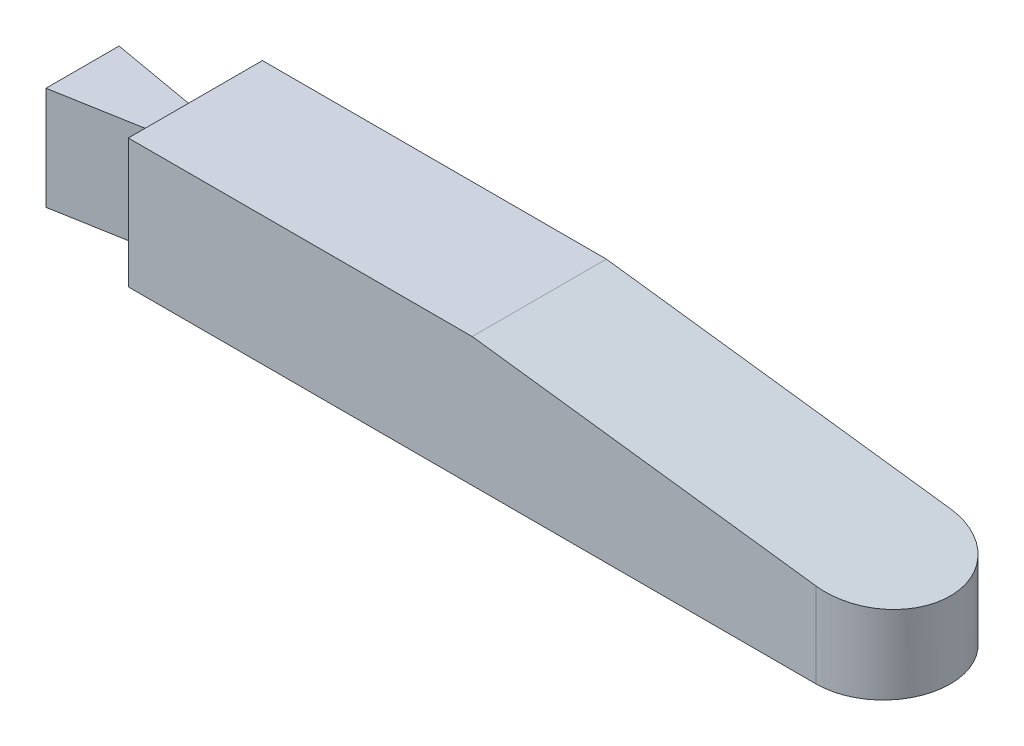
SolidWorks part; units mm, degrees
ref_plane "Front Plane" through (0, 0, 0) normal (0, 0, 1) x (1, 0, 0)
ref_plane "Top Plane" through (0, 0, 0) normal (0, 1, 0) x (1, 0, 0)
ref_plane "Right Plane" through (0, 0, 0) normal (1, 0, 0) x (0, 0, -1)
sketch "Sketch2" plane through (0, 0, 0) normal (0, 1, 0) x (1, 0, 0)
  line L10 (18.9628, -17.9605) -> (18.9628, -28.085) construction
  line L29 (-13.5492, -12.2277) -> (-13.5492, -33.8177)
  line L30 (-13.5492, -12.2277) -> (18.9628, -17.9605)
  line L31 (-13.5492, -33.8177) -> (18.9628, -28.085)
  line L32 (18.9628, -2.3886) -> (222.1628, -2.3886)
  line L33 (18.9628, -42.0126) -> (222.1628, -42.0126)
  line L35 (18.9628, -2.3886) -> (18.9628, -17.9605)
  line L36 (18.9628, -42.0126) -> (18.9628, -28.085)
  line L37 (-13.5492, -23.0227) -> (18.9628, -23.0227) construction
  arc A5 (222.1628, -2.3886) -> (222.1628, -42.0126) centre (222.1628, -22.2006) cw
  dimension "D4" = 80
  dimension "D5" = 39.624
  dimension "D3" = 80
  dimension "D2" = 21.59
  dimension "D6" = 203.2
  dimension "D9" = 13.5492
  dimension "D10" = 26.1183
  dimension "D11" = 13.9276
  dimension "D14" = 32.512
extrude "Boss-Extrude1" add sketch "Sketch2" along normal blind 38.1
sketch "Sketch3" plane through (0, 38.1, 0) normal (0, 1, 0) x (1, 0, 0)
  line L0 (-13.5492, -12.2277) -> (-13.5492, -33.8177)
  line L1 (-13.5492, -33.8177) -> (18.9628, -28.085)
  line L2 (18.9628, -28.085) -> (18.9628, -17.9605)
  line L3 (18.9628, -17.9605) -> (-13.5492, -12.2277)
extrude "Cut-Extrude1" cut sketch "Sketch3" against normal blind 7.62
sketch "Sketch5" plane through (0, 0, 42.0126) normal (0, 0, 1) x (1, 0, 0)
  line L5 (120.5628, 38.1) -> (241.9748, 22.5197)
  line L6 (18.9628, 38.1) -> (222.1628, 38.1) construction
  line L7 (241.9748, 0) -> (241.9748, 38.1) construction
  line L8 (241.9748, 22.5197) -> (241.9748, 38.1)
  line L9 (241.9748, 38.1) -> (120.5628, 38.1)
  dimension "D1" = 7.313
extrude "Cut-Extrude4" cut sketch "Sketch5" against normal blind 39.624
